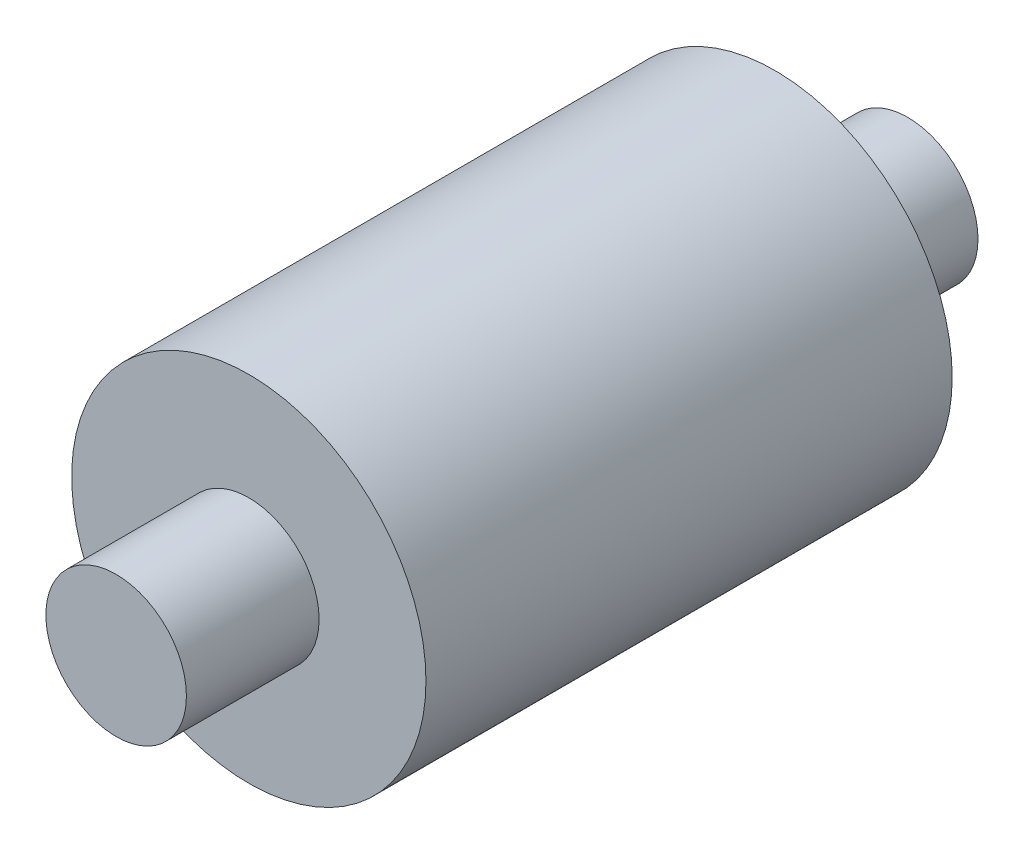
SolidWorks part; units mm, degrees
ref_plane "Front Plane" through (0, 0, 0) normal (0, 0, 1) x (1, 0, 0)
ref_plane "Top Plane" through (0, 0, 0) normal (0, 1, 0) x (1, 0, 0)
ref_plane "Right Plane" through (0, 0, 0) normal (1, 0, 0) x (0, 0, -1)
sketch "Sketch1" plane through (0, 0, 0) normal (0, 0, 1) x (1, 0, 0)
  circle A0 centre (0, 0) radius 1.5875
  dimension "D1" = 3.175
extrude "Boss-Extrude1" add sketch "Sketch1" against normal blind 17.8816
ref_plane "Plane1" through (0, 0, -2.9972) normal (0, 0, 1) x (1, 0, 0)
sketch "Sketch2" plane through (0, 0, -2.9972) normal (0, 0, 1) x (1, 0, 0)
  circle A0 centre (0, 0) radius 4.0015
  dimension "D1" = 8.003
extrude "Boss-Extrude2" add sketch "Sketch2" against normal blind 11.8872
